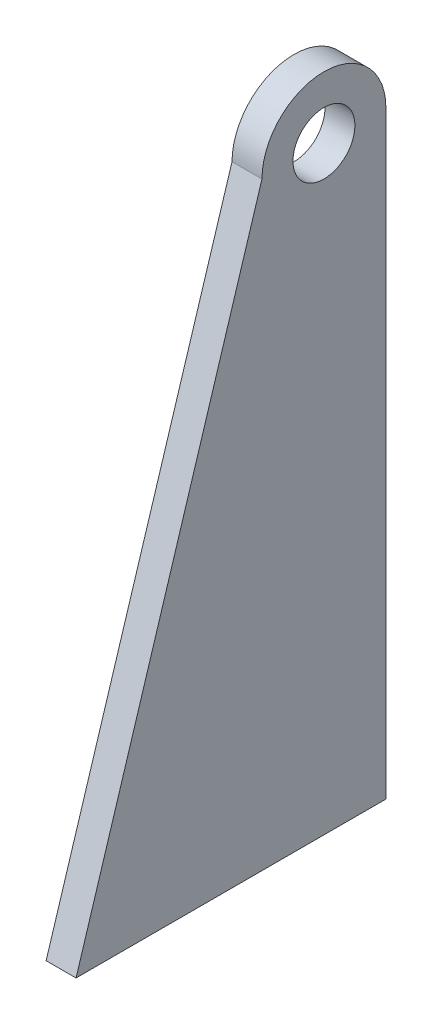
SolidWorks part; units mm, degrees
ref_plane "Front Plane" through (0, 0, 0) normal (0, 0, 1) x (1, 0, 0)
ref_plane "Top Plane" through (0, 0, 0) normal (0, 1, 0) x (1, 0, 0)
ref_plane "Right Plane" through (0, 0, 0) normal (1, 0, 0) x (0, 0, -1)
sketch "Sketch2" plane through (0, 0, 0) normal (1, 0, 0) x (0, 0, -1)
  line L0 (0, 0) -> (60, 0)
  line L1 (60, 0) -> (60, 116)
  line L2 (36, 116) -> (0, 0)
  arc A0 (60, 116) -> (36, 116) centre (48, 116) ccw
  circle A1 centre (48, 116) radius 6
  dimension "D3" = 24
  dimension "D4" = 12
  dimension "D1" = 60
  dimension "D2" = 116
extrude "Boss-Extrude1" add sketch "Sketch2" along normal blind 5.8
